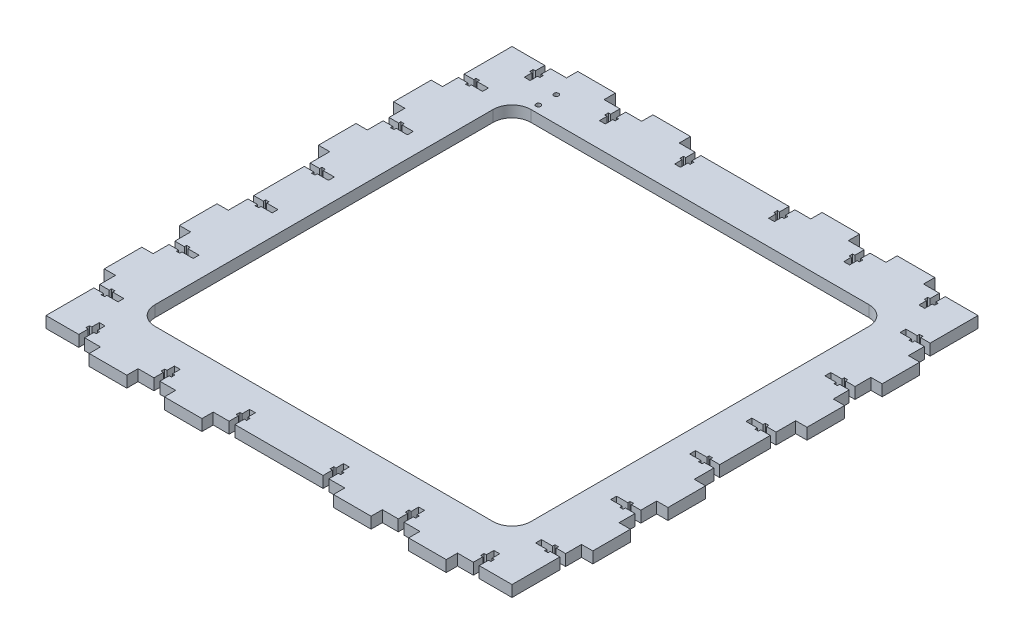
SolidWorks part; units mm, degrees
ref_plane "Front Plane" through (0, 0, 0) normal (0, 0, 1) x (1, 0, 0)
ref_plane "Top Plane" through (0, 0, 0) normal (0, 1, 0) x (1, 0, 0)
ref_plane "Right Plane" through (0, 0, 0) normal (1, 0, 0) x (0, 0, -1)
sketch "Sketch1" plane through (0, 0, 0) normal (0, 1, 0) x (1, 0, 0)
  line L0 (130, 260) -> (130, 0) construction
  line L1 (0, 0) -> (260, 0)
  line L2 (0, 0) -> (0, 260)
  line L3 (0, 260) -> (260, 260)
  line L4 (260, 0) -> (260, 260)
  line L5 (0, 260) -> (260, 260)
  line L6 (0, 260) -> (0, 254)
  line L7 (0, 254) -> (260, 254)
  line L8 (260, 260) -> (260, 254)
  line L9 (35, 260) -> (55, 260)
  line L10 (35, 260) -> (35, 254)
  line L11 (35, 254) -> (55, 254)
  line L12 (55, 260) -> (55, 254)
  line L13 (75, 254) -> (95, 254)
  line L14 (75, 254) -> (75, 260)
  line L15 (75, 260) -> (95, 260)
  line L16 (95, 254) -> (95, 260)
  line L17 (0, 130) -> (260, 130) construction
  line L18 (73, 230) -> (177.06, 230) construction
  line L19 (0, 260) -> (6, 260)
  line L20 (0, 260) -> (0, 0)
  line L21 (0, 0) -> (6, 0)
  line L22 (6, 260) -> (6, 0)
  line L23 (0, 217) -> (6, 217)
  line L24 (0, 217) -> (0, 197)
  line L25 (0, 197) -> (6, 197)
  line L26 (6, 217) -> (6, 197)
  line L27 (6, 177) -> (0, 177)
  line L28 (6, 177) -> (6, 157)
  line L29 (6, 157) -> (0, 157)
  line L30 (0, 177) -> (0, 157)
  line L31 (185, 260) -> (165, 260)
  line L32 (130, 214.5) -> (114.5, 214.5) construction
  line L34 (130, 245.5) -> (114.5, 245.5) construction
  line L35 (114.5, 214.5) -> (114.5, 245.5) construction
  line L36 (130, 230) -> (114.5, 245.5) construction
  line L37 (130, 230) -> (114.5, 214.5) construction
  line L38 (80.5, 222.5) -> (65.5, 222.5) construction
  line L39 (80.5, 222.5) -> (80.5, 237.5) construction
  line L40 (80.5, 237.5) -> (65.5, 237.5) construction
  line L41 (65.5, 222.5) -> (65.5, 237.5) construction
  line L42 (80.5, 222.5) -> (65.5, 237.5) construction
  line L43 (80.5, 237.5) -> (65.5, 222.5) construction
  line L44 (165, 254) -> (165, 260)
  line L45 (185, 254) -> (165, 254)
  line L46 (185, 254) -> (185, 260)
  line L47 (225, 254) -> (205, 254)
  line L48 (205, 260) -> (205, 254)
  line L49 (225, 260) -> (205, 260)
  line L50 (225, 260) -> (225, 254)
  line L51 (254, 157) -> (260, 157)
  line L52 (260, 177) -> (260, 157)
  line L53 (254, 177) -> (260, 177)
  line L54 (254, 177) -> (254, 157)
  line L55 (260, 197) -> (254, 197)
  line L56 (254, 217) -> (254, 197)
  line L57 (260, 217) -> (254, 217)
  line L58 (260, 217) -> (260, 197)
  line L59 (254, 83) -> (254, 103)
  line L60 (254, 83) -> (260, 83)
  line L61 (260, 83) -> (260, 103)
  line L62 (254, 103) -> (260, 103)
  line L63 (260, 43) -> (260, 63)
  line L64 (260, 43) -> (254, 43)
  line L65 (254, 43) -> (254, 63)
  line L66 (260, 63) -> (254, 63)
  line L67 (225, 0) -> (225, 6)
  line L68 (225, 0) -> (205, 0)
  line L69 (205, 0) -> (205, 6)
  line L70 (225, 6) -> (205, 6)
  line L71 (185, 6) -> (185, 0)
  line L72 (185, 6) -> (165, 6)
  line L73 (165, 6) -> (165, 0)
  line L74 (185, 0) -> (165, 0)
  line L75 (75, 0) -> (95, 0)
  line L76 (95, 6) -> (95, 0)
  line L77 (75, 6) -> (95, 6)
  line L78 (75, 6) -> (75, 0)
  line L79 (35, 6) -> (55, 6)
  line L80 (55, 0) -> (55, 6)
  line L81 (35, 0) -> (55, 0)
  line L82 (35, 0) -> (35, 6)
  line L83 (0, 63) -> (6, 63)
  line L84 (6, 43) -> (6, 63)
  line L85 (0, 43) -> (6, 43)
  line L86 (0, 43) -> (0, 63)
  line L87 (6, 103) -> (0, 103)
  line L88 (0, 83) -> (0, 103)
  line L89 (6, 83) -> (0, 83)
  line L90 (6, 83) -> (6, 103)
  line L91 (254, 260) -> (254, 0)
  line L92 (0, 6) -> (254, 6)
  point P29 (3, 217)
  point P30 (3, 157)
  point P31 (3, 177)
  dimension "D16" = 15.5
  dimension "D1" = 260
  dimension "D2" = 260
  dimension "D3" = 6
  dimension "D4" = 20
  dimension "D5" = 20
  dimension "D6" = 20
  dimension "D7" = 29
  dimension "D8" = 6
  dimension "D9" = 20
  dimension "D10" = 20
  dimension "D11" = 20
  dimension "D12" = 37
  dimension "D15" = 31
  dimension "D18" = 24
  dimension "D19" = 57
  dimension "D20" = 15
  dimension "D21" = 15
extrude "Boss-Extrude1" add sketch "Sketch1" along normal blind 6
sketch "Sketch2" plane through (0, 6, 0) normal (0, 1, 0) x (1, 0, 0)
  line L0 (6, 254) -> (35, 254) construction
  line L1 (23.45, 254) -> (26.55, 254)
  line L2 (23.45, 254) -> (23.45, 249)
  line L3 (23.45, 243.1) -> (26.55, 243.1)
  line L4 (26.55, 254) -> (26.55, 249)
  line L5 (103.45, 254) -> (106.55, 254)
  line L6 (26.55, 249) -> (27.75, 249)
  line L7 (22.25, 247.1) -> (23.45, 247.1)
  line L8 (22.25, 247.1) -> (22.25, 249)
  line L9 (22.25, 249) -> (23.45, 249)
  line L10 (27.75, 247.1) -> (27.75, 249)
  line L11 (23.45, 247.1) -> (23.45, 243.1)
  line L12 (26.55, 247.1) -> (27.75, 247.1)
  line L13 (26.55, 247.1) -> (26.55, 243.1)
  line L14 (45, 260) -> (45, 264.9812) construction
  line L15 (35, 260) -> (55, 260) construction
  line L28 (103.45, 254) -> (103.45, 249)
  line L29 (103.45, 243.1) -> (106.55, 243.1)
  line L30 (25, 243.1) -> (25, 260.914) construction
  line L31 (65, 243.1) -> (65, 260.914) construction
  line L32 (63.45, 247.1) -> (63.45, 243.1)
  line L33 (63.45, 247.1) -> (62.25, 247.1)
  line L34 (66.55, 247.1) -> (66.55, 243.1)
  line L35 (62.25, 247.1) -> (62.25, 249)
  line L36 (67.75, 249) -> (66.55, 249)
  line L37 (67.75, 247.1) -> (67.75, 249)
  line L38 (67.75, 247.1) -> (66.55, 247.1)
  line L39 (63.45, 249) -> (62.25, 249)
  line L40 (63.45, 254) -> (63.45, 249)
  line L41 (66.55, 243.1) -> (63.45, 243.1)
  line L42 (66.55, 254) -> (66.55, 249)
  line L43 (66.55, 254) -> (63.45, 254)
  line L44 (85, 260) -> (85, 268.4526) construction
  line L45 (75, 260) -> (95, 260) construction
  line L46 (106.55, 254) -> (106.55, 249)
  line L47 (106.55, 249) -> (107.75, 249)
  line L48 (102.25, 247.1) -> (103.45, 247.1)
  line L49 (102.25, 247.1) -> (102.25, 249)
  line L50 (102.25, 249) -> (103.45, 249)
  line L51 (107.75, 247.1) -> (107.75, 249)
  line L52 (103.45, 247.1) -> (103.45, 243.1)
  line L53 (106.55, 247.1) -> (107.75, 247.1)
  line L54 (106.55, 247.1) -> (106.55, 243.1)
  line L55 (130, 254) -> (130, 268.4526) construction
  line L56 (95, 254) -> (165, 254) construction
  line L62 (175, 260) -> (175, 268.4526) construction
  line L78 (195, 243.1) -> (195, 260.914) construction
  line L87 (235, 243.1) -> (235, 260.914) construction
  line L89 (215, 260) -> (215, 264.9812) construction
  line L98 (153.45, 247.1) -> (153.45, 243.1)
  line L99 (153.45, 247.1) -> (152.25, 247.1)
  line L100 (156.55, 247.1) -> (156.55, 243.1)
  line L101 (152.25, 247.1) -> (152.25, 249)
  line L102 (157.75, 249) -> (156.55, 249)
  line L103 (157.75, 247.1) -> (157.75, 249)
  line L104 (157.75, 247.1) -> (156.55, 247.1)
  line L105 (153.45, 249) -> (152.25, 249)
  line L106 (153.45, 254) -> (153.45, 249)
  line L107 (193.45, 254) -> (196.55, 254)
  line L108 (193.45, 254) -> (193.45, 249)
  line L109 (193.45, 243.1) -> (196.55, 243.1)
  line L110 (196.55, 254) -> (196.55, 249)
  line L111 (196.55, 249) -> (197.75, 249)
  line L112 (192.25, 247.1) -> (193.45, 247.1)
  line L113 (192.25, 247.1) -> (192.25, 249)
  line L114 (192.25, 249) -> (193.45, 249)
  line L115 (197.75, 247.1) -> (197.75, 249)
  line L116 (193.45, 247.1) -> (193.45, 243.1)
  line L117 (196.55, 247.1) -> (197.75, 247.1)
  line L118 (196.55, 247.1) -> (196.55, 243.1)
  line L119 (156.55, 243.1) -> (153.45, 243.1)
  line L120 (156.55, 254) -> (156.55, 249)
  line L121 (233.45, 247.1) -> (233.45, 243.1)
  line L122 (233.45, 247.1) -> (232.25, 247.1)
  line L123 (236.55, 247.1) -> (236.55, 243.1)
  line L124 (232.25, 247.1) -> (232.25, 249)
  line L125 (237.75, 249) -> (236.55, 249)
  line L126 (237.75, 247.1) -> (237.75, 249)
  line L127 (237.75, 247.1) -> (236.55, 247.1)
  line L128 (233.45, 249) -> (232.25, 249)
  line L129 (156.55, 254) -> (153.45, 254)
  line L130 (233.45, 254) -> (233.45, 249)
  line L131 (236.55, 243.1) -> (233.45, 243.1)
  line L132 (236.55, 254) -> (236.55, 249)
  line L133 (236.55, 254) -> (233.45, 254)
  line L134 (6, 130) -> (-18.5109, 130) construction
  line L135 (6, 157) -> (6, 103) construction
  line L136 (215, 0) -> (215, -4.9812) construction
  line L137 (235, 16.9) -> (235, -0.914) construction
  line L138 (195, 16.9) -> (195, -0.914) construction
  line L139 (175, 0) -> (175, -8.4526) construction
  line L140 (130, 6) -> (130, -8.4526) construction
  line L141 (85, 0) -> (85, -8.4526) construction
  line L142 (65, 16.9) -> (65, -0.914) construction
  line L143 (25, 16.9) -> (25, -0.914) construction
  line L144 (45, 0) -> (45, -4.9812) construction
  line L145 (236.55, 6) -> (233.45, 6)
  line L146 (236.55, 6) -> (236.55, 11)
  line L147 (236.55, 16.9) -> (233.45, 16.9)
  line L148 (233.45, 6) -> (233.45, 11)
  line L149 (156.55, 6) -> (153.45, 6)
  line L150 (233.45, 11) -> (232.25, 11)
  line L151 (237.75, 12.9) -> (236.55, 12.9)
  line L152 (237.75, 12.9) -> (237.75, 11)
  line L153 (237.75, 11) -> (236.55, 11)
  line L154 (232.25, 12.9) -> (232.25, 11)
  line L155 (236.55, 12.9) -> (236.55, 16.9)
  line L156 (233.45, 12.9) -> (232.25, 12.9)
  line L157 (233.45, 12.9) -> (233.45, 16.9)
  line L158 (156.55, 6) -> (156.55, 11)
  line L159 (156.55, 16.9) -> (153.45, 16.9)
  line L160 (196.55, 12.9) -> (196.55, 16.9)
  line L161 (196.55, 12.9) -> (197.75, 12.9)
  line L162 (193.45, 12.9) -> (193.45, 16.9)
  line L163 (197.75, 12.9) -> (197.75, 11)
  line L164 (192.25, 11) -> (193.45, 11)
  line L165 (192.25, 12.9) -> (192.25, 11)
  line L166 (192.25, 12.9) -> (193.45, 12.9)
  line L167 (196.55, 11) -> (197.75, 11)
  line L168 (196.55, 6) -> (196.55, 11)
  line L169 (193.45, 16.9) -> (196.55, 16.9)
  line L170 (193.45, 6) -> (193.45, 11)
  line L171 (193.45, 6) -> (196.55, 6)
  line L172 (153.45, 6) -> (153.45, 11)
  line L173 (153.45, 11) -> (152.25, 11)
  line L174 (157.75, 12.9) -> (156.55, 12.9)
  line L175 (157.75, 12.9) -> (157.75, 11)
  line L176 (157.75, 11) -> (156.55, 11)
  line L177 (152.25, 12.9) -> (152.25, 11)
  line L178 (156.55, 12.9) -> (156.55, 16.9)
  line L179 (153.45, 12.9) -> (152.25, 12.9)
  line L180 (153.45, 12.9) -> (153.45, 16.9)
  line L181 (106.55, 12.9) -> (106.55, 16.9)
  line L182 (106.55, 12.9) -> (107.75, 12.9)
  line L183 (103.45, 12.9) -> (103.45, 16.9)
  line L184 (107.75, 12.9) -> (107.75, 11)
  line L185 (102.25, 11) -> (103.45, 11)
  line L186 (102.25, 12.9) -> (102.25, 11)
  line L187 (102.25, 12.9) -> (103.45, 12.9)
  line L188 (106.55, 11) -> (107.75, 11)
  line L189 (106.55, 6) -> (106.55, 11)
  line L190 (66.55, 6) -> (63.45, 6)
  line L191 (66.55, 6) -> (66.55, 11)
  line L192 (66.55, 16.9) -> (63.45, 16.9)
  line L193 (63.45, 6) -> (63.45, 11)
  line L194 (63.45, 11) -> (62.25, 11)
  line L195 (67.75, 12.9) -> (66.55, 12.9)
  line L196 (67.75, 12.9) -> (67.75, 11)
  line L197 (67.75, 11) -> (66.55, 11)
  line L198 (62.25, 12.9) -> (62.25, 11)
  line L199 (66.55, 12.9) -> (66.55, 16.9)
  line L200 (63.45, 12.9) -> (62.25, 12.9)
  line L201 (63.45, 12.9) -> (63.45, 16.9)
  line L202 (103.45, 16.9) -> (106.55, 16.9)
  line L203 (103.45, 6) -> (103.45, 11)
  line L204 (26.55, 12.9) -> (26.55, 16.9)
  line L205 (26.55, 12.9) -> (27.75, 12.9)
  line L206 (23.45, 12.9) -> (23.45, 16.9)
  line L207 (27.75, 12.9) -> (27.75, 11)
  line L208 (22.25, 11) -> (23.45, 11)
  line L209 (22.25, 12.9) -> (22.25, 11)
  line L210 (22.25, 12.9) -> (23.45, 12.9)
  line L211 (26.55, 11) -> (27.75, 11)
  line L212 (103.45, 6) -> (106.55, 6)
  line L213 (26.55, 6) -> (26.55, 11)
  line L214 (23.45, 16.9) -> (26.55, 16.9)
  line L215 (23.45, 6) -> (23.45, 11)
  line L216 (23.45, 6) -> (26.55, 6)
  dimension "D1" = 3.1
  dimension "D2" = 20
  dimension "D3" = 1.9
  dimension "D4" = 5
  dimension "D5" = 4
  dimension "D6" = 5.5
  dimension "D7" = 1.2
extrude "Cut-Extrude1" cut sketch "Sketch2" against normal blind 10
sketch "Sketch3" plane through (0, 6, 0) normal (0, 1, 0) x (1, 0, 0)
  line L0 (6, 130) -> (279.3265, 130) construction
  line L1 (6, 157) -> (6, 103) construction
  line L2 (6, 254) -> (6, 217) construction
  line L3 (6, 228.55) -> (11.1, 228.55)
  line L4 (6, 228.55) -> (6, 225.45)
  line L5 (6, 225.45) -> (11.1, 225.45)
  line L6 (18.9, 228.55) -> (18.9, 225.45)
  line L7 (18.9, 187) -> (-3.2582, 187) construction
  line L8 (18.9, 115) -> (-3.7345, 115) construction
  line L9 (18.9, 227) -> (-6.1, 227) construction
  line L10 (12.9, 225.45) -> (12.9, 224.25)
  line L11 (12.9, 229.75) -> (11.1, 229.75)
  line L12 (12.9, 229.75) -> (12.9, 228.55)
  line L13 (12.9, 224.25) -> (11.1, 224.25)
  line L14 (11.1, 229.75) -> (11.1, 228.55)
  line L15 (12.9, 228.55) -> (18.9, 228.55)
  line L16 (11.1, 225.45) -> (11.1, 224.25)
  line L17 (12.9, 225.45) -> (18.9, 225.45)
  line L18 (12.9, 188.55) -> (18.9, 188.55)
  line L19 (11.1, 188.55) -> (11.1, 189.75)
  line L20 (12.9, 185.45) -> (18.9, 185.45)
  line L21 (11.1, 184.25) -> (11.1, 185.45)
  line L22 (12.9, 189.75) -> (11.1, 189.75)
  line L23 (12.9, 184.25) -> (12.9, 185.45)
  line L24 (12.9, 184.25) -> (11.1, 184.25)
  line L25 (12.9, 188.55) -> (12.9, 189.75)
  line L26 (18.9, 185.45) -> (18.9, 188.55)
  line L27 (6, 188.55) -> (11.1, 188.55)
  line L28 (6, 185.45) -> (6, 188.55)
  line L29 (6, 185.45) -> (11.1, 185.45)
  line L31 (6, 146.55) -> (11.1, 146.55)
  line L32 (6, 146.55) -> (6, 143.45)
  line L33 (6, 143.45) -> (11.1, 143.45)
  line L34 (18.9, 146.55) -> (18.9, 143.45)
  line L35 (12.9, 143.45) -> (12.9, 142.25)
  line L36 (12.9, 147.75) -> (11.1, 147.75)
  line L37 (12.9, 147.75) -> (12.9, 146.55)
  line L38 (12.9, 142.25) -> (11.1, 142.25)
  line L39 (11.1, 147.75) -> (11.1, 146.55)
  line L40 (12.9, 146.55) -> (18.9, 146.55)
  line L41 (11.1, 143.45) -> (11.1, 142.25)
  line L42 (12.9, 143.45) -> (18.9, 143.45)
  line L43 (18.9, 145) -> (-3.7345, 145) construction
  line L44 (18.9, 33) -> (-6.1, 33) construction
  line L45 (18.9, 73) -> (-3.2582, 73) construction
  line L46 (12.9, 116.55) -> (18.9, 116.55)
  line L47 (11.1, 116.55) -> (11.1, 117.75)
  line L48 (12.9, 113.45) -> (18.9, 113.45)
  line L49 (11.1, 112.25) -> (11.1, 113.45)
  line L50 (12.9, 117.75) -> (11.1, 117.75)
  line L51 (12.9, 112.25) -> (12.9, 113.45)
  line L52 (12.9, 112.25) -> (11.1, 112.25)
  line L53 (12.9, 116.55) -> (12.9, 117.75)
  line L54 (18.9, 113.45) -> (18.9, 116.55)
  line L55 (6, 116.55) -> (11.1, 116.55)
  line L56 (6, 113.45) -> (6, 116.55)
  line L57 (6, 113.45) -> (11.1, 113.45)
  line L58 (6, 74.55) -> (11.1, 74.55)
  line L59 (6, 74.55) -> (6, 71.45)
  line L60 (6, 71.45) -> (11.1, 71.45)
  line L61 (18.9, 74.55) -> (18.9, 71.45)
  line L62 (12.9, 71.45) -> (12.9, 70.25)
  line L63 (12.9, 75.75) -> (11.1, 75.75)
  line L64 (12.9, 75.75) -> (12.9, 74.55)
  line L65 (12.9, 70.25) -> (11.1, 70.25)
  line L66 (11.1, 75.75) -> (11.1, 74.55)
  line L67 (12.9, 74.55) -> (18.9, 74.55)
  line L68 (11.1, 71.45) -> (11.1, 70.25)
  line L69 (12.9, 71.45) -> (18.9, 71.45)
  line L70 (12.9, 34.55) -> (18.9, 34.55)
  line L71 (11.1, 34.55) -> (11.1, 35.75)
  line L72 (12.9, 31.45) -> (18.9, 31.45)
  line L73 (11.1, 30.25) -> (11.1, 31.45)
  line L74 (12.9, 35.75) -> (11.1, 35.75)
  line L75 (12.9, 30.25) -> (12.9, 31.45)
  line L76 (12.9, 30.25) -> (11.1, 30.25)
  line L77 (12.9, 34.55) -> (12.9, 35.75)
  line L78 (18.9, 31.45) -> (18.9, 34.55)
  line L79 (6, 34.55) -> (11.1, 34.55)
  line L80 (6, 31.45) -> (6, 34.55)
  line L81 (6, 31.45) -> (11.1, 31.45)
  line L82 (130, 254) -> (130, 6) construction
  line L83 (106.55, 254) -> (153.45, 254) construction
  line L84 (106.55, 6) -> (153.45, 6) construction
  line L85 (241.1, 73) -> (263.2582, 73) construction
  line L86 (241.1, 33) -> (266.1, 33) construction
  line L87 (241.1, 145) -> (263.7345, 145) construction
  line L88 (241.1, 227) -> (266.1, 227) construction
  line L89 (241.1, 115) -> (263.7345, 115) construction
  line L90 (241.1, 187) -> (263.2582, 187) construction
  line L91 (254, 31.45) -> (248.9, 31.45)
  line L92 (254, 31.45) -> (254, 34.55)
  line L93 (254, 34.55) -> (248.9, 34.55)
  line L94 (241.1, 31.45) -> (241.1, 34.55)
  line L95 (247.1, 34.55) -> (247.1, 35.75)
  line L96 (247.1, 30.25) -> (248.9, 30.25)
  line L97 (247.1, 30.25) -> (247.1, 31.45)
  line L98 (247.1, 35.75) -> (248.9, 35.75)
  line L99 (248.9, 30.25) -> (248.9, 31.45)
  line L100 (247.1, 31.45) -> (241.1, 31.45)
  line L101 (248.9, 34.55) -> (248.9, 35.75)
  line L102 (247.1, 34.55) -> (241.1, 34.55)
  line L103 (247.1, 71.45) -> (241.1, 71.45)
  line L104 (248.9, 71.45) -> (248.9, 70.25)
  line L105 (247.1, 74.55) -> (241.1, 74.55)
  line L106 (248.9, 75.75) -> (248.9, 74.55)
  line L107 (247.1, 70.25) -> (248.9, 70.25)
  line L108 (247.1, 75.75) -> (247.1, 74.55)
  line L109 (247.1, 75.75) -> (248.9, 75.75)
  line L110 (247.1, 71.45) -> (247.1, 70.25)
  line L111 (241.1, 74.55) -> (241.1, 71.45)
  line L112 (254, 71.45) -> (248.9, 71.45)
  line L113 (254, 74.55) -> (254, 71.45)
  line L114 (254, 74.55) -> (248.9, 74.55)
  line L115 (254, 113.45) -> (248.9, 113.45)
  line L116 (254, 113.45) -> (254, 116.55)
  line L117 (254, 116.55) -> (248.9, 116.55)
  line L118 (241.1, 113.45) -> (241.1, 116.55)
  line L119 (247.1, 116.55) -> (247.1, 117.75)
  line L120 (247.1, 112.25) -> (248.9, 112.25)
  line L121 (247.1, 112.25) -> (247.1, 113.45)
  line L122 (247.1, 117.75) -> (248.9, 117.75)
  line L123 (248.9, 112.25) -> (248.9, 113.45)
  line L124 (247.1, 113.45) -> (241.1, 113.45)
  line L125 (248.9, 116.55) -> (248.9, 117.75)
  line L126 (247.1, 116.55) -> (241.1, 116.55)
  line L127 (247.1, 143.45) -> (241.1, 143.45)
  line L128 (248.9, 143.45) -> (248.9, 142.25)
  line L129 (247.1, 146.55) -> (241.1, 146.55)
  line L130 (248.9, 147.75) -> (248.9, 146.55)
  line L131 (247.1, 142.25) -> (248.9, 142.25)
  line L132 (247.1, 147.75) -> (247.1, 146.55)
  line L133 (247.1, 147.75) -> (248.9, 147.75)
  line L134 (247.1, 143.45) -> (247.1, 142.25)
  line L135 (241.1, 146.55) -> (241.1, 143.45)
  line L136 (254, 143.45) -> (248.9, 143.45)
  line L137 (254, 146.55) -> (254, 143.45)
  line L138 (254, 146.55) -> (248.9, 146.55)
  line L139 (254, 185.45) -> (248.9, 185.45)
  line L140 (254, 185.45) -> (254, 188.55)
  line L141 (254, 188.55) -> (248.9, 188.55)
  line L142 (241.1, 185.45) -> (241.1, 188.55)
  line L143 (247.1, 188.55) -> (247.1, 189.75)
  line L144 (247.1, 184.25) -> (248.9, 184.25)
  line L145 (247.1, 184.25) -> (247.1, 185.45)
  line L146 (247.1, 189.75) -> (248.9, 189.75)
  line L147 (248.9, 184.25) -> (248.9, 185.45)
  line L148 (247.1, 185.45) -> (241.1, 185.45)
  line L149 (248.9, 188.55) -> (248.9, 189.75)
  line L150 (247.1, 188.55) -> (241.1, 188.55)
  line L151 (247.1, 225.45) -> (241.1, 225.45)
  line L152 (248.9, 225.45) -> (248.9, 224.25)
  line L153 (247.1, 228.55) -> (241.1, 228.55)
  line L154 (248.9, 229.75) -> (248.9, 228.55)
  line L155 (247.1, 224.25) -> (248.9, 224.25)
  line L156 (247.1, 229.75) -> (247.1, 228.55)
  line L157 (247.1, 229.75) -> (248.9, 229.75)
  line L158 (247.1, 225.45) -> (247.1, 224.25)
  line L159 (241.1, 228.55) -> (241.1, 225.45)
  line L160 (254, 225.45) -> (248.9, 225.45)
  line L161 (254, 228.55) -> (254, 225.45)
  line L162 (254, 228.55) -> (248.9, 228.55)
  dimension "D1" = 12.9
  dimension "D2" = 3.1
  dimension "D3" = 5.5
  dimension "D4" = 2.75
  dimension "D5" = 1.8
  dimension "D6" = 6
  dimension "D7" = 42
  dimension "D8" = 40
  dimension "D9" = 15
extrude "Cut-Extrude2" cut sketch "Sketch3" against normal blind 10
sketch "Sketch4" plane through (0, 6, 0) normal (0, 1, 0) x (1, 0, 0)
  line L0 (35, 260) -> (-10.0844, 260) construction
  line L1 (0, 217) -> (0, 260) construction
  line L2 (260, 217) -> (260, 197) construction
  line L3 (0, 260) -> (260, 260)
  line L4 (0, 260) -> (0, 0)
  line L5 (0, 0) -> (260, 0)
  line L6 (260, 260) -> (260, 0)
  line L7 (0, 260) -> (260, 0) construction
  line L8 (0, 0) -> (260, 260) construction
  line L10 (230, 30) -> (30, 30)
  line L11 (230, 30) -> (230, 230)
  line L12 (230, 230) -> (30, 230)
  line L13 (30, 30) -> (30, 230)
  line L14 (230, 30) -> (30, 230) construction
  line L15 (230, 230) -> (30, 30) construction
  point P12 (130, 130)
  dimension "D1" = 0
  dimension "D2" = 200
extrude "Cut-Extrude3" cut sketch "Sketch4" against normal blind 10 contours L11 L10 L13 L12
fillet "Fillet1" radius 10 4 edges at (30, 3, -30) (230, 3, -30) (230, 3, -230) (30, 3, -230)
sketch "Sketch5" plane through (0, 6, 0) normal (0, 1, 0) x (1, 0, 0)
  line L0 (40, 286.3393) -> (40, 216.4301) construction
  line L1 (0, 197) -> (0, 217) construction
  line L2 (-19.1169, 234) -> (103.9588, 234) construction
  line L3 (35, 260) -> (55, 260) construction
  circle A0 centre (40, 234) radius 1.25
  circle A1 centre (40, 243.6) radius 1.25
  point P8 (40, 234)
  dimension "D3" = 2.5
  dimension "D4" = 2.5
  dimension "D5" = 9.6
  dimension "D1" = 40
  dimension "D2" = 26
extrude "Cut-Extrude5" cut sketch "Sketch5" against normal blind 10
